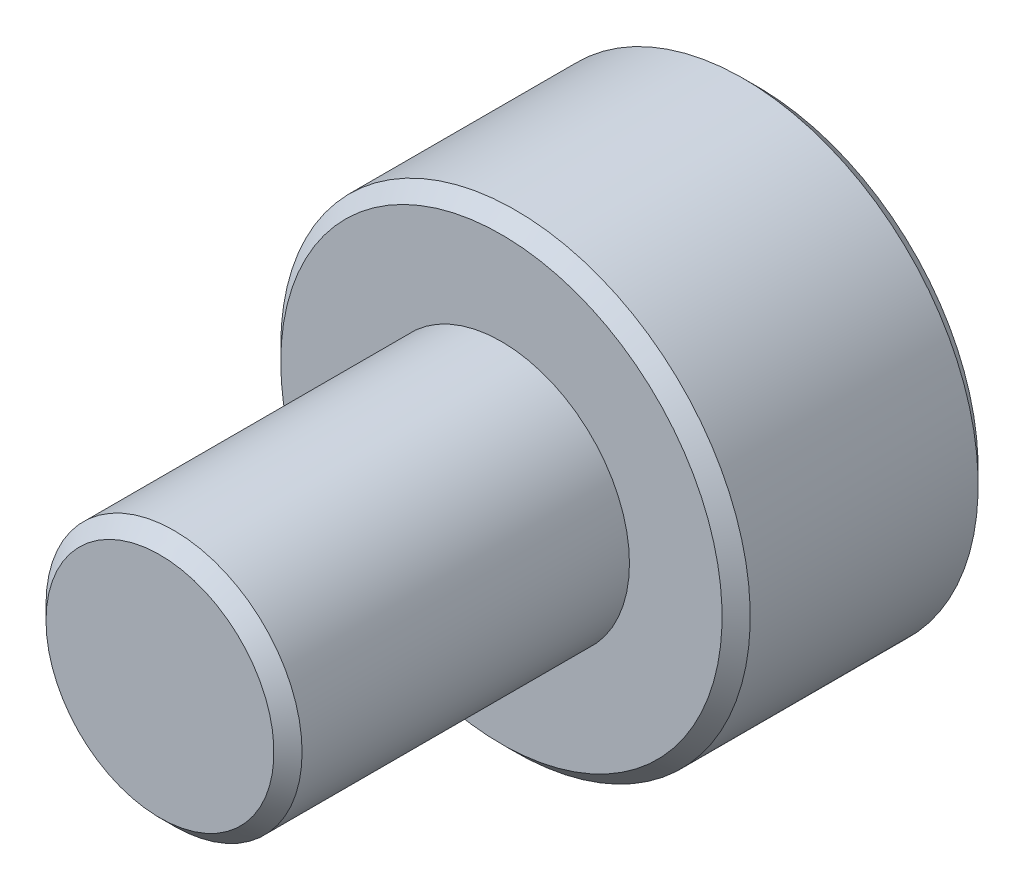
SolidWorks part; units mm, degrees
material "Alloy Steel"
ref_plane "Front Plane" through (0, 0, 0) normal (0, 0, 1) x (1, 0, 0)
ref_plane "Top Plane" through (0, 0, 0) normal (0, 1, 0) x (1, 0, 0)
ref_plane "Right Plane" through (0, 0, 0) normal (1, 0, 0) x (0, 0, -1)
sketch "Sketch1" plane through (0, 0, 0) normal (0, 0, 1) x (1, 0, 0)
  circle A0 centre (0, 0) radius 1.5
  dimension "OD" = 3
extrude "Extrude1" add sketch "Sketch1" against normal blind 4
sketch "Sketch2" plane through (0, 0, 0) normal (0, 0, 1) x (1, 0, 0)
  circle A0 centre (0, 0) radius 1.5 construction
  circle A1 centre (0, 0) radius 1.5
curve "Helix/Spiral1" pitch 0.5 height 4.5 turns 9 parameters "pitch"=0.5
sketch "Sketch3" plane through (0, 0, 0) normal (1, 0, 0) x (0, 0, -1)
  line L0 (-0.4375, 1.5) -> (-0.25, 1.1752)
  line L1 (-0.25, 1.1752) -> (-0.1875, 1.1752)
  line L2 (-0.1875, 1.1752) -> (0, 1.5)
  line L3 (-0.4375, 1.5) -> (0, 1.5)
  line L4 (-0.2187, 1.5) -> (-0.2187, 1.1752) construction
  line L5 (-0.3437, 1.3376) -> (-0.0937, 1.3376) construction
  line L6 (0, 1.5) -> (0, -1.5) construction
  line L7 (0, -1.5) -> (4, -1.5) construction
  point P11 (2.25, -1.5)
  dimension "D1" = 0.0625
  dimension "D2" = 0.25
  dimension "D3" = 60
  dimension "D4" = 2.25
sketch "Sketch6" plane through (0, 0, -4) normal (0, 0, -1) x (-1, 0, 0)
  circle A0 centre (0, 0) radius 2.75
  dimension "head dia" = 5.5
extrude "Extrude2" add sketch "Sketch6" along normal blind 3
sketch "Sketch7" plane through (0, 0, -7) normal (0, 0, -1) x (-1, 0, 0)
  line L1 (0, 1.4434) -> (-1.25, 0.7217)
  line L2 (-1.25, 0.7217) -> (-1.25, -0.7217)
  line L3 (-1.25, -0.7217) -> (0, -1.4434)
  line L4 (0, -1.4434) -> (1.25, -0.7217)
  line L5 (1.25, -0.7217) -> (1.25, 0.7217)
  line L6 (1.25, 0.7217) -> (0, 1.4434)
  circle A0 centre (0, 0) radius 1.25 construction
  dimension "hex dia" = 2.5
extrude "Cut-Extrude1" cut sketch "Sketch7" against normal blind 1.875
sketch "Sketch8" plane through (0, 0, -7) normal (0, 0, -1) x (-1, 0, 0)
  circle A0 centre (0, 0) radius 1.4434
extrude "Cut-Extrude2" cut sketch "Sketch8" against normal through all draft 45
chamfer "Chamfer1" distance 0.165 angle 45 3 edges at (-2.75, 0, -7) (-2.75, 0, -4) (1.5, 0, 0)
sketch "Sketch9" plane through (0, 0, 0) normal (1, 0, 0) x (0, 0, -1)
  line L0 (0, 1.5) -> (0, -1.5) construction
  line L1 (2.75, 1.5) -> (2.75, -1.5) construction
  dimension "D1" = 2.75
sketch "Sketch10" plane through (0, 0, 0) normal (1, 0, 0) x (0, 0, -1)
  line L0 (4, 1.5) -> (4, 0)
  line L1 (4, 1.5) -> (3.875, 1.5)
  line L2 (3.875, 1.5) -> (3.2537, 0)
  line L3 (4, 0) -> (3.2537, 0)
  line L4 (4, 2.585) -> (4, -2.585) construction
  dimension "D1" = 22.5
  dimension "D2" = 0.125
equation "\"D3@Helix/Spiral1\" = \"screw length@Extrude1\"+\"pitch@Helix/Spiral1\""
equation "\"D1@Sketch3\" = \"pitch@Helix/Spiral1\"*.125"
equation "\"D2@Sketch3\" = \"pitch@Helix/Spiral1\"*.5"
equation "\"D1@Cut-Extrude1\" = \"hex dia@Sketch7\"*.75"
equation "\"D1@Chamfer1\" = \"head dia@Sketch6\"*.03"
equation "\"D1@Sketch9\" = \"pitch@Helix/Spiral1\"*5.5"
equation "\"D2@Sketch10\" = \"pitch@Helix/Spiral1\"*.25"
equation "\"D4@Sketch3\" = \"pitch@Helix/Spiral1\"*4.50"
